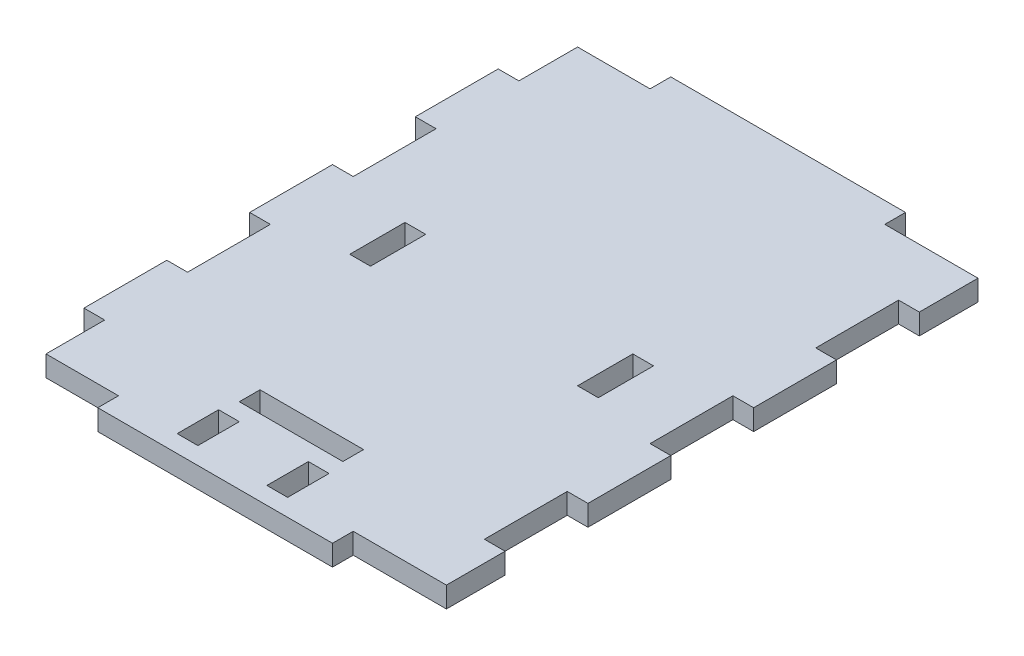
SolidWorks part; units mm, degrees
ref_plane "Alzado" through (0, 0, 0) normal (0, 0, 1) x (1, 0, 0)
ref_plane "Planta" through (0, 0, 0) normal (0, 1, 0) x (1, 0, 0)
ref_plane "Vista lateral" through (0, 0, 0) normal (1, 0, 0) x (0, 0, -1)
sketch "Croquis1" plane through (0, 0, 0) normal (0, 1, 0) x (1, 0, 0)
  line L0 (13.5, 0) -> (47.5, 0)
  line L1 (30.5, 0) -> (13.5, 0)
  line L2 (30.5, 0) -> (47.5, 0)
  line L3 (47.5, 0) -> (47.5, 3)
  line L4 (58, 35.5) -> (58, 47.5)
  line L5 (13.5, 3) -> (13.5, 0)
  line L6 (61, 3) -> (61, 11.5)
  line L7 (0, 11.5) -> (0, 23.5)
  line L8 (61, 23.5) -> (61, 35.5)
  line L9 (13.5, 80) -> (13.5, 83)
  line L10 (58, 47.5) -> (61, 47.5)
  line L11 (47.5, 83) -> (47.5, 80)
  line L12 (13.5, 83) -> (47.5, 83)
  line L13 (13.5, 80) -> (3, 80)
  line L14 (47.5, 80) -> (61, 80)
  line L15 (13.5, 3) -> (3, 3)
  line L16 (47.5, 3) -> (61, 3)
  line L17 (61, 47.5) -> (61, 59.5)
  line L18 (61, 59.5) -> (58, 59.5)
  line L19 (58, 59.5) -> (58, 71.5)
  line L20 (58, 71.5) -> (61, 71.5)
  line L21 (58, 11.5) -> (61, 11.5)
  line L22 (58, 23.5) -> (58, 11.5)
  line L23 (61, 23.5) -> (58, 23.5)
  line L24 (58, 35.5) -> (61, 35.5)
  line L26 (3, 35.5) -> (0, 35.5)
  line L27 (0, 23.5) -> (3, 23.5)
  line L29 (3, 11.5) -> (0, 11.5)
  line L30 (3, 71.5) -> (0, 71.5)
  line L31 (3, 11.5) -> (3, 3)
  line L32 (0, 59.5) -> (3, 59.5)
  line L33 (3, 47.5) -> (0, 47.5)
  line L36 (3, 80) -> (3, 71.5)
  line L37 (61, 71.5) -> (61, 80)
  line L38 (61, 47.5) -> (61, 59.5)
  line L39 (0, 59.5) -> (0, 71.5)
  line L40 (0, 35.5) -> (0, 47.5)
  line L41 (3, 59.5) -> (3, 47.5)
  line L42 (3, 35.5) -> (3, 23.5)
  dimension "D3" = 17
  dimension "D4" = 3
  dimension "D5" = 12
  dimension "D6" = 12
extrude "Saliente-Extruir1" add sketch "Croquis1" along normal blind 3 contours L26 L42 L27 L7 L29 L31 L15 L5 L0 L3 L16 L6 L21 L22 L23 L8 L24 L4 L10 L17 L18 L19 L20 L37 L14 L11 L12 L9 L13 L36 L30 L39 L32 L41 L33 L40
sketch "Croquis2" plane through (0, 3, 0) normal (0, 1, 0) x (1, 0, 0)
  line L0 (45.5, 41.5) -> (15.5, 41.5) construction
  line L1 (15.5, 41.5) -> (15.5, 45.5)
  line L2 (15.5, 45.5) -> (12.5, 45.5)
  line L3 (12.5, 45.5) -> (12.5, 37.5)
  line L4 (12.5, 37.5) -> (15.5, 37.5)
  line L5 (15.5, 37.5) -> (15.5, 41.5)
  line L6 (45.5, 37.5) -> (45.5, 41.5)
  line L7 (30.5, 83) -> (30.5, 0) construction
  line L8 (48.5, 37.5) -> (45.5, 37.5)
  line L9 (48.5, 45.5) -> (48.5, 37.5)
  line L10 (45.5, 45.5) -> (48.5, 45.5)
  line L11 (45.5, 41.5) -> (45.5, 45.5)
  line L12 (30.5, 41.5) -> (30.5, 14) construction
  line L13 (13.5, 83) -> (47.5, 83) construction
  line L14 (30.5, 14) -> (23, 14)
  line L15 (13.5, 0) -> (47.5, 0) construction
  line L16 (23, 14) -> (23, 11)
  line L17 (24, 11) -> (24, 0) construction
  line L18 (38, 11) -> (38, 14)
  line L19 (38, 14) -> (30.5, 14)
  line L20 (25, 11) -> (23, 11)
  line L21 (35.5, 8.5) -> (35.5, 2.5)
  line L22 (22.5, 5.5) -> (22.5, 8.5)
  line L23 (22.5, 8.5) -> (25.5, 8.5)
  line L24 (25.5, 8.5) -> (25.5, 2.5)
  line L25 (25.5, 2.5) -> (22.5, 2.5)
  line L26 (22.5, 2.5) -> (22.5, 5.5)
  line L27 (35.5, 2.5) -> (38.5, 2.5)
  line L28 (38.5, 2.5) -> (38.5, 5.5)
  line L29 (38.5, 5.5) -> (38.5, 8.5)
  line L30 (38.5, 8.5) -> (35.5, 8.5)
  line L31 (25, 11) -> (38, 11)
  point P17 (30.5, 41.5)
  dimension "D1" = 15
  dimension "D2" = 4
  dimension "D3" = 3
  dimension "D4" = 8
  dimension "D5" = 27.5
  dimension "D6" = 7.5
  dimension "D7" = 3
  dimension "D8" = 15
  dimension "D10" = 3
  dimension "D11" = 3
  dimension "D12" = 6
extrude "Cortar-Extruir1" cut sketch "Croquis2" against normal blind 10
